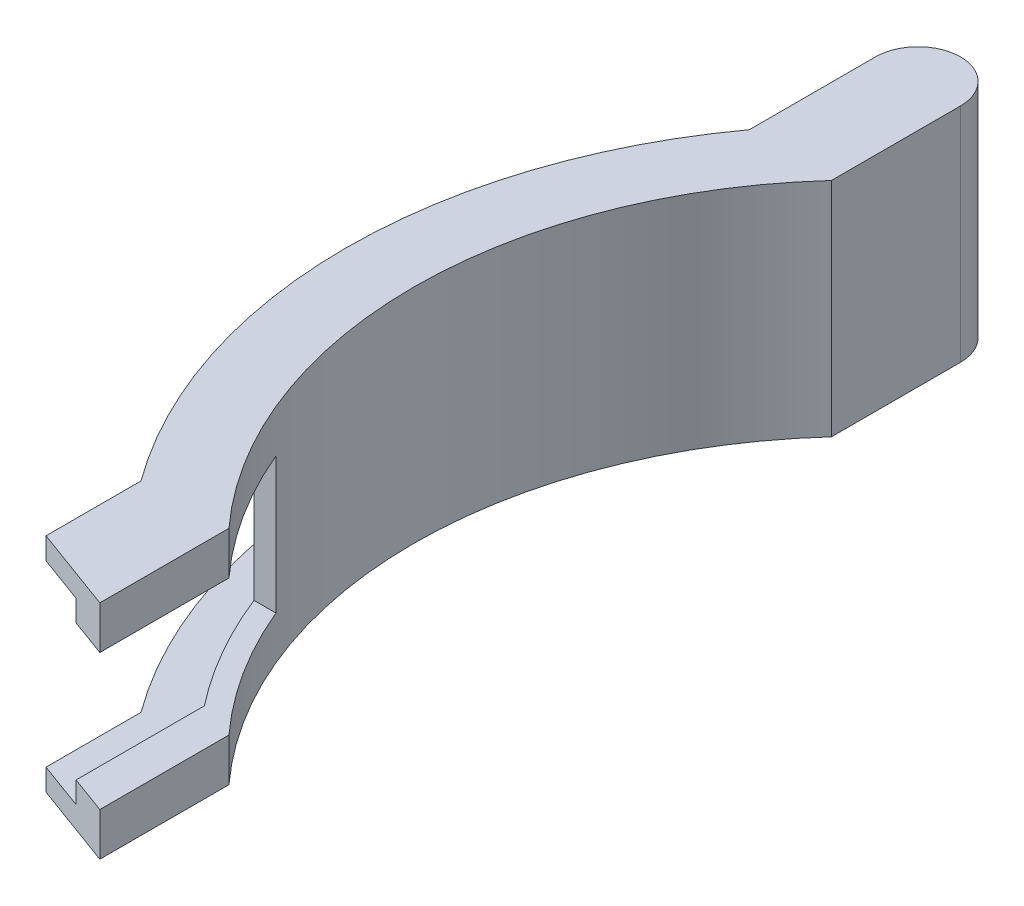
SolidWorks part; units mm, degrees
ref_plane "Plan de face" through (0, 0, 0) normal (0, 0, 1) x (1, 0, 0)
ref_plane "Plan de dessus" through (0, 0, 0) normal (0, 1, 0) x (1, 0, 0)
ref_plane "Plan de droite" through (0, 0, 0) normal (1, 0, 0) x (0, 0, -1)
ref_plane "Plan4" through (0, 13.208, 0) normal (0, -1, 0) x (1, 0, 0)
sketch "Esquisse1" plane through (0, 13.208, 0) normal (0, -1, 0) x (1, 0, 0)
  line L0 (20.6502, 3.175) -> (20.6502, 12.7)
  line L1 (20.6502, 12.7) -> (17.8802, 11.6849)
  line L2 (17.8802, 11.6849) -> (17.8802, 2.2173)
  line L3 (17.8802, -40.3173) -> (17.8802, -41.4911)
  line L4 (17.8802, -41.4911) -> (20.6502, -41.4911)
  line L5 (20.6502, -41.4911) -> (20.6502, -41.275)
  arc A0 (20.6502, -41.275) -> (20.6502, 3.175) centre (45.0709, -19.05) cw
  arc A1 (17.8802, 2.2173) -> (17.8802, -40.3173) centre (45.0709, -19.05) ccw
extrude "Boss.-Extru.1" add sketch "Esquisse1" against normal blind 1.575
sketch "Esquisse2" plane through (0, 14.783, 0) normal (0, 1, 0) x (-1, 0, 0)
  line L0 (-14.3802, -41.4911) -> (-20.6502, -41.4911)
  line L1 (-20.6502, -41.4911) -> (-20.6502, -41.275)
  line L2 (-20.6502, 3.175) -> (-20.6502, 12.7)
  line L3 (-20.6502, 12.7) -> (-14.3802, 10.4024)
  line L4 (-14.3802, 10.4024) -> (-14.3802, 3.3911)
  arc A0 (-20.6502, -41.275) -> (-20.6502, 3.175) centre (-45.0709, -19.05) ccw
  arc A1 (-14.3802, 3.3911) -> (-14.3802, -41.4911) centre (-45.0709, -19.05) cw
extrude "Boss.-Extru.2" add sketch "Esquisse2" along normal blind 1.6
sketch "Esquisse3" plane through (0, 13.208, 0) normal (0, -1, 0) x (1, 0, 0)
  line L0 (12.972, -6.35) -> (14.5909, -6.35)
  line L1 (20.6502, -41.275) -> (20.6502, -41.4911)
  line L2 (20.6502, -41.4911) -> (17.8802, -41.4911)
  line L3 (17.8802, -41.4911) -> (17.8802, -40.3173)
  arc A0 (14.5909, -6.35) -> (20.6502, -41.275) centre (45.0709, -19.05) ccw
  arc A1 (17.8802, -40.3173) -> (12.972, -6.35) centre (45.0709, -19.05) cw
extrude "Boss.-Extru.3" add sketch "Esquisse3" along normal blind 10.033
sketch "Esquisse4" plane through (0, 3.175, 0) normal (0, -1, 0) x (1, 0, 0)
  line L0 (17.8802, -41.4911) -> (17.8802, -40.3173)
  line L1 (17.8802, 2.2173) -> (17.8802, 11.6849)
  line L2 (17.8802, 11.6849) -> (20.6502, 12.7)
  line L3 (20.6502, 12.7) -> (20.6502, 3.175)
  line L4 (20.6502, -41.275) -> (20.6502, -41.4911)
  line L5 (20.6502, -41.4911) -> (17.8802, -41.4911)
  arc A0 (17.8802, -40.3173) -> (17.8802, 2.2173) centre (45.0709, -19.05) cw
  arc A1 (20.6502, 3.175) -> (20.6502, -41.275) centre (45.0709, -19.05) ccw
extrude "Boss.-Extru.4" add sketch "Esquisse4" along normal blind 1.575
sketch "Esquisse5" plane through (0, 0, -41.4911) normal (0, 0, -1) x (-1, 0, 0)
  line L0 (-20.6502, 1.6) -> (-20.6502, 16.383)
  line L1 (-20.6502, 16.383) -> (-14.3802, 16.383)
  line L2 (-14.3802, 16.383) -> (-14.3802, 14.783)
  line L3 (-14.3802, 14.783) -> (-17.8802, 14.783)
  line L4 (-17.8802, 14.783) -> (-17.8802, 1.6)
  line L5 (-17.8802, 1.6) -> (-20.6502, 1.6)
extrude "Boss.-Extru.5" add sketch "Esquisse5" along normal blind 9.3089
sketch "Esquisse6" plane through (0, 1.6, 0) normal (0, -1, 0) x (1, 0, 0)
  line L0 (20.6502, -41.275) -> (20.6502, -50.8)
  line L1 (20.6502, -50.8) -> (14.3802, -50.8)
  line L2 (14.3802, -50.8) -> (14.3802, -41.4911)
  line L3 (14.3802, 3.3911) -> (14.3802, 10.4024)
  line L4 (14.3802, 10.4024) -> (20.6502, 12.7)
  line L5 (20.6502, 12.7) -> (20.6502, 3.175)
  arc A0 (20.6502, 3.175) -> (20.6502, -41.275) centre (45.0709, -19.05) ccw
  arc A1 (14.3802, -41.4911) -> (14.3802, 3.3911) centre (45.0709, -19.05) cw
extrude "Boss.-Extru.6" add sketch "Esquisse6" along normal blind 1.6
sketch "Esquisse8" plane through (0, 16.383, 0) normal (0, 1, 0) x (1, 0, 0)
  line L0 (14.3802, 50.8) -> (20.6502, 50.8) construction
  circle A0 centre (17.5152, 50.8) radius 3.135
extrude "Boss.-Extru.7" add sketch "Esquisse8" against normal up to surface (16.383 mm away) contours A0
